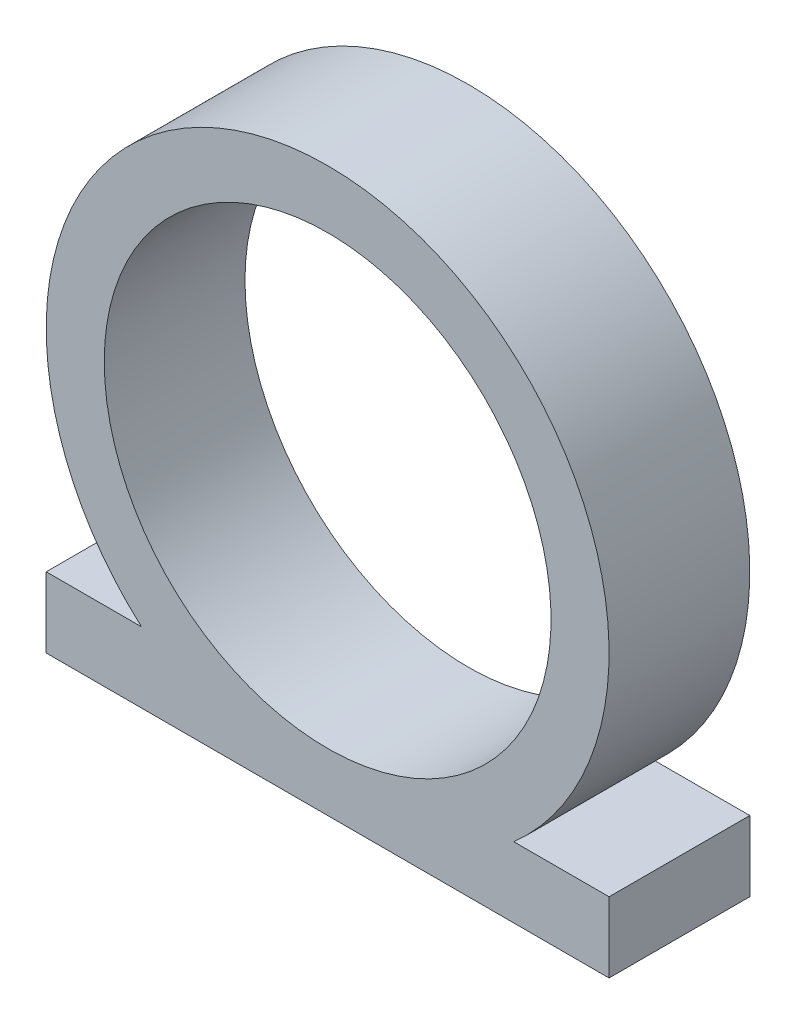
SolidWorks part; units mm, degrees
ref_plane "Front Plane" through (0, 0, 0) normal (0, 0, 1) x (1, 0, 0)
ref_plane "Top Plane" through (0, 0, 0) normal (0, 1, 0) x (1, 0, 0)
ref_plane "Right Plane" through (0, 0, 0) normal (1, 0, 0) x (0, 0, -1)
sketch "Sketch1" plane through (0, 0, 0) normal (0, 0, 1) x (1, 0, 0)
  circle A0 centre (0, 0) radius 20
  dimension "D1" = 40
extrude "Boss-Extrude1" add sketch "Sketch1" along normal blind 10
sketch "Sketch2" plane through (0, 0, 0) normal (0, 0, -1) x (-1, 0, 0)
  line L1 (20, -15) -> (-20, -15)
  line L2 (20, -15) -> (20, -20)
  line L3 (20, -20) -> (-20, -20)
  line L4 (-20, -15) -> (-20, -20)
  circle A0 centre (0, 0) radius 20 construction
  dimension "D2" = 20
  dimension "D1" = 5
  dimension "D3" = 40
  dimension "D4" = 20
extrude "Boss-Extrude2" add sketch "Sketch2" against normal blind 10
sketch "Sketch3" plane through (0, 0, 0) normal (0, 0, -1) x (-1, 0, 0)
  circle A0 centre (0, 0) radius 15.875
  dimension "D1" = 31.75
extrude "Cut-Extrude1" cut sketch "Sketch3" against normal through all
